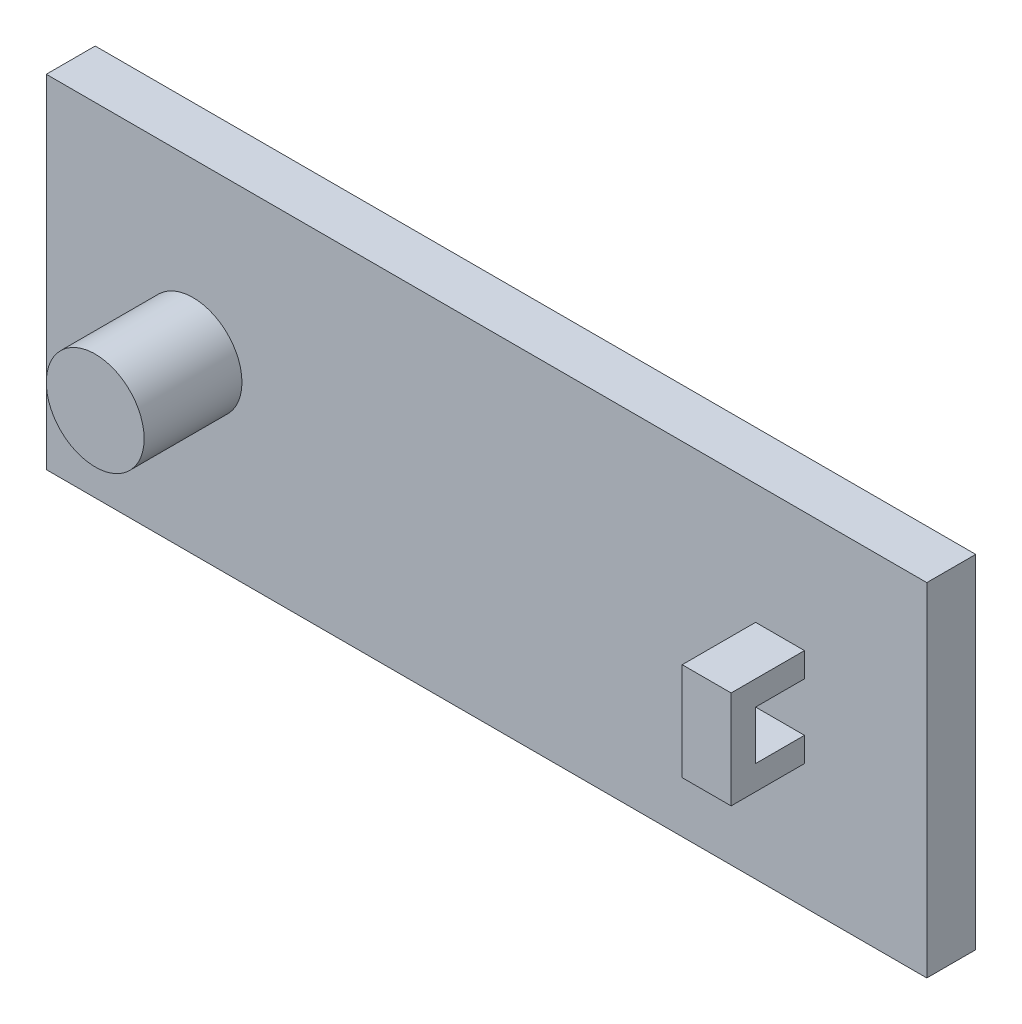
SolidWorks part; units mm, degrees
ref_plane "前视基准面" through (0, 0, 0) normal (0, 0, 1) x (1, 0, 0)
ref_plane "上视基准面" through (0, 0, 0) normal (0, 1, 0) x (1, 0, 0)
ref_plane "右视基准面" through (0, 0, 0) normal (1, 0, 0) x (0, 0, -1)
sketch "草图1" plane through (0, 0, 0) normal (0, 0, 1) x (1, 0, 0)
  line L1 (-14.5324, 5.4153) -> (3.4676, 5.4153)
  line L2 (-14.5324, 5.4153) -> (-14.5324, -1.5847)
  line L3 (-14.5324, -1.5847) -> (3.4676, -1.5847)
  line L4 (3.4676, 5.4153) -> (3.4676, -1.5847)
  line L5 (-14.5324, 5.4153) -> (3.4676, -1.5847) construction
  line L6 (-14.5324, -1.5847) -> (3.4676, 5.4153) construction
  point P0 (-5.5324, 1.9153)
  dimension "D1" = 18
  dimension "D2" = 7
extrude "凸台-拉伸1" add sketch "草图1" along normal blind 1
sketch "草图3" plane through (0, 0, 1) normal (0, 0, 1) x (1, 0, 0)
  line L0 (-14.5324, 5.4153) -> (-14.5324, -1.5847) construction
  circle A0 centre (-11.5324, 1.9619) radius 1
  dimension "D1" = 2
  dimension "D2" = 3
extrude "凸台-拉伸2" add sketch "草图3" along normal blind 2
ref_plane "基准面4" through (0.4676, 0, 0) normal (1, 0, 0) x (0, 0, -1)
sketch "草图7" plane through (0.4676, 0, 0) normal (1, 0, 0) x (0, 0, -1)
  line L0 (-2.5, 0.9619) -> (-1, 0.9619)
  line L1 (-2, 1.4619) -> (-1, 1.4619)
  line L2 (-2, 1.4619) -> (-2, 2.4619)
  line L3 (-2, 2.4619) -> (-1, 2.4619)
  line L8 (-2.5, 2.9619) -> (-1, 2.9619)
  line L9 (-2.5, 0.9619) -> (-2.5, 2.9619)
  line L10 (-1, 0.9619) -> (-1, 1.4619)
  line L11 (-2.5, 2.9619) -> (-0.5, 2.9619) construction
  line L12 (-2.5, 0.9619) -> (-0.5, 0.9619) construction
  line L13 (-0.5, 0.9619) -> (-0.5, 2.9619) construction
  line L16 (-1, 1.4619) -> (-1, 2.4619) construction
  line L17 (-1, 2.4619) -> (-1, 2.9619)
  point P0 (-1.5, 1.9619)
  point P11 (0, 0)
  dimension "D1" = 1
  dimension "D2" = 1
  dimension "D3" = 0.5
extrude "凸台-拉伸4" add sketch "草图7" along normal mid plane 1
